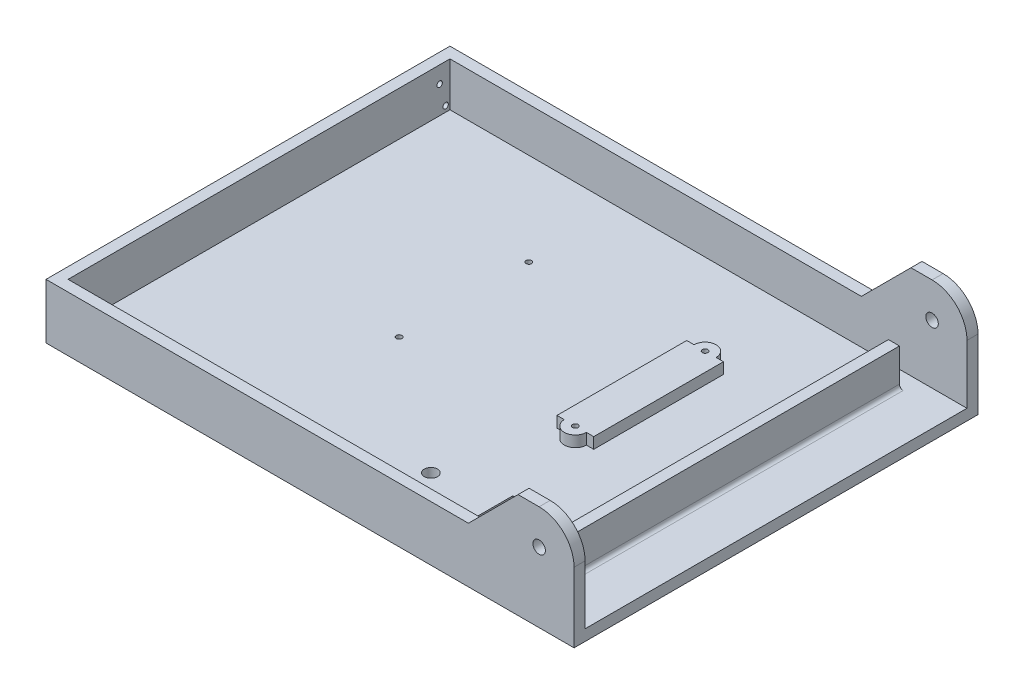
SolidWorks part; units mm, degrees
ref_plane "前视基准面" through (0, 0, 0) normal (0, 0, 1) x (1, 0, 0)
ref_plane "上视基准面" through (0, 0, 0) normal (0, 1, 0) x (1, 0, 0)
ref_plane "右视基准面" through (0, 0, 0) normal (1, 0, 0) x (0, 0, -1)
sketch "草图1" plane through (0, 0, 0) normal (0, 0, 1) x (1, 0, 0)
  line L0 (113.913, -6.4015) -> (113.913, -22.4015)
  line L1 (113.913, -22.4015) -> (104.413, -22.4015)
  line L2 (104.413, 3.0985) -> (98.6738, 3.0985)
  line L3 (104.413, -22.4015) -> (-26.7592, -22.4015)
  line L5 (-30.7592, -10.4015) -> (83.0524, -10.4015) construction
  line L6 (83.0524, -10.4015) -> (97.0524, 3.5985) construction
  line L7 (-22.7592, -21.4015) -> (-22.7592, 2.5985) construction
  line L8 (-22.7592, -21.4015) -> (-22.7592, 2.5985) construction
  line L9 (104.413, -6.4015) -> (104.413, -22.4015) construction
  line L10 (83.0524, -10.4015) -> (96.3453, 2.8914) construction
  line L11 (95.6382, 3.5985) -> (112.413, 3.5985)
  line L12 (-29.7592, 2.0985) -> (-29.7592, -9.4015)
  line L13 (-29.7592, -9.4015) -> (82.6382, -9.4015)
  line L14 (82.6382, -9.4015) -> (95.6382, 3.5985)
  line L15 (95.6382, 3.5985) -> (112.413, 3.5985) construction
  line L16 (-29.7592, 2.0985) -> (-29.7592, -9.4015) construction
  line L17 (-29.7592, -9.4015) -> (82.6382, -9.4015) construction
  line L18 (82.6382, -9.4015) -> (95.6382, 3.5985) construction
  line L20 (83.0524, -10.4015) -> (-26.7592, -10.4015)
  line L21 (-26.7592, -10.4015) -> (-26.7592, -22.4015)
  line L22 (98.6738, 3.0985) -> (85.1738, -10.4015)
  line L23 (-24.7592, -21.4015) -> (102.413, -21.4015)
  line L24 (112.413, -11.4015) -> (112.413, 3.5985)
  line L25 (112.413, 3.5985) -> (95.6382, 3.5985)
  line L26 (95.6382, 3.5985) -> (82.6382, -9.4015)
  line L27 (82.6382, -9.4015) -> (-24.7592, -9.4015)
  line L28 (-24.7592, -9.4015) -> (-24.7592, -21.4015)
  line L29 (-24.7592, -21.4015) -> (102.413, -21.4015) construction
  line L30 (112.413, -11.4015) -> (112.413, 3.5985) construction
  line L31 (112.413, 3.5985) -> (95.6382, 3.5985) construction
  line L32 (95.6382, 3.5985) -> (82.6382, -9.4015) construction
  line L33 (82.6382, -9.4015) -> (-24.7592, -9.4015) construction
  line L34 (-24.7592, -9.4015) -> (-24.7592, -21.4015) construction
  line L35 (-30.7592, 2.0985) -> (-30.7592, -10.4015) construction
  line L36 (85.1738, -10.4015) -> (83.0524, -10.4015)
  line L57 (112.413, 3.5985) -> (112.413, 5.5985)
  line L58 (112.413, 3.5985) -> (112.413, 5.5985)
  line L59 (112.413, 5.5985) -> (-32.7592, 5.5985)
  line L60 (112.413, 5.5985) -> (-32.7592, 5.5985)
  line L69 (-29.7592, -9.4015) -> (-29.7592, 2.0985) construction
  line L148 (-32.7592, 5.5985) -> (-32.7592, 2.0985)
  line L149 (-32.7592, 5.5985) -> (-32.7592, 2.0985)
  line L150 (-32.7592, 2.0985) -> (-29.7592, 2.0985)
  line L151 (-32.7592, 2.0985) -> (-29.7592, 2.0985)
  circle A0 centre (104.413, -6.4015) radius 9.5 construction
  arc A1 (113.913, -6.4015) -> (104.413, 3.0985) centre (104.413, -6.4015) ccw
  arc A2 (102.413, -21.4015) -> (112.413, -11.4015) centre (102.413, -11.4015) ccw
  arc A3 (102.413, -21.4015) -> (112.413, -11.4015) centre (102.413, -11.4015) ccw construction
  dimension "D1" = 19
  dimension "D2" = 0
  dimension "D4" = 3
  dimension "D6" = 2.5
  dimension "D7" = 1
  dimension "D3" = 0
  dimension "D5" = 1
extrude "凸台-拉伸1" add sketch "草图1" against normal offset from surface (103.9078 mm away) 1
shell "抽壳1" thickness 3
sketch "草图2" plane through (0, 0, 3) normal (0, 0, 1) x (1, 0, 0)
  line L6 (113.913, -25.4015) -> (113.913, -6.4015)
  line L7 (104.413, 3.0985) -> (98.6738, 3.0985)
  line L8 (98.6738, 3.0985) -> (85.1738, -10.4015)
  line L10 (-29.7592, -10.4015) -> (-29.7592, -25.4015)
  line L11 (-29.7592, -25.4015) -> (113.913, -25.4015)
  line L12 (113.913, -25.4015) -> (113.913, -6.4015)
  line L14 (98.6738, 3.0985) -> (85.1738, -10.4015)
  line L16 (-29.7592, -10.4015) -> (-29.7592, -25.4015)
  line L17 (-29.7592, -25.4015) -> (113.913, -25.4015)
  line L18 (104.413, 3.0985) -> (98.6738, 3.0985)
  line L21 (85.1738, -10.4015) -> (-29.7592, -10.4015)
  line L22 (85.1738, -10.4015) -> (-29.7592, -10.4015)
  circle A0 centre (104.413, -6.4015) radius 2 construction
  arc A1 (113.913, -6.4015) -> (104.413, 3.0985) centre (104.413, -6.4015) ccw
  arc A2 (113.913, -6.4015) -> (104.413, 3.0985) centre (104.413, -6.4015) ccw
  circle A3 centre (104.413, -6.4015) radius 2 construction
  dimension "D1" = 0
hole_wizard "M3 间隙孔1" positions "草图3" profile "草图4" hole size "M3" standard "GB"
sketch "草图3" plane through (0, 0, 3) normal (0, 0, 1) x (1, 0, 0)
  point P0 (104.413, -6.4015)
sketch "草图4" plane through (104.413, -6.4015, 3) normal (1, 0, 0) x (0, -1, 0)
  line L0 (0, 0) -> (0, 110.9282)
  line L1 (0, 110.9282) -> (1.7, 109.9068)
  line L2 (1.7, 109.9068) -> (1.7, 0)
  line L5 (1.7, 0) -> (0, 0)
  line L10 (0, 110.9282) -> (-1.7, 109.9068) construction
  line L11 (0, -6.35) -> (0, 107.95) construction
  dimension "孔直径" = 3.4
  dimension "孔深度" = 109.9068
  dimension "导头角度" = 118
sketch "草图6" plane through (0, -22.4015, 0) normal (0, 1, 0) x (1, 0, 0)
  line L0 (100.0439, 3.5) -> (97.0439, 3.5)
  line L1 (100.0439, 99.4078) -> (97.0439, 99.4078)
  line L2 (100.0439, 99.4078) -> (100.0439, 3.5)
  line L3 (97.0439, 3.5) -> (97.0439, 99.4078)
  line L6 (97.0439, 41.2959) -> (97.0439, 3)
  line L7 (97.0439, 85.8578) -> (97.0439, 41.2959)
  line L8 (97.0439, 99.9078) -> (97.0439, 85.8578)
  line L9 (100.0439, 99.9078) -> (97.0439, 99.9078)
  line L10 (100.0439, 3) -> (100.0439, 99.9078)
  line L11 (97.0439, 3) -> (100.0439, 3)
  line L12 (97.0439, 41.2959) -> (97.0439, 3) construction
  line L13 (97.0439, 85.8578) -> (97.0439, 41.2959) construction
  line L14 (97.0439, 99.9078) -> (97.0439, 85.8578) construction
  line L15 (100.0439, 99.9078) -> (97.0439, 99.9078) construction
  line L16 (100.0439, 3) -> (100.0439, 99.9078) construction
  line L17 (97.0439, 3) -> (100.0439, 3) construction
  dimension "D2" = 0.5
  dimension "D3" = 0.5
  dimension "D1" = 0
extrude "凸台-拉伸2" add sketch "草图6" along normal offset from surface (10 mm away) 1
sketch "草图10" plane through (0, -22.4015, 0) normal (0, 1, 0) x (1, 0, 0)
  line L0 (63.5653, 79.1078) -> (72.0573, 79.1078) construction
  line L1 (74.5549, 76.6078) -> (74.5549, 45.6078) construction
  line L2 (72.0573, 43.1078) -> (63.5653, 43.1078) construction
  line L3 (61.0676, 45.6078) -> (61.0676, 76.6078) construction
  line L4 (13.1129, 45.6078) -> (13.1129, 76.6078) construction
  line L5 (15.6106, 79.1078) -> (24.1026, 79.1078) construction
  line L6 (26.6002, 76.6078) -> (26.6002, 45.6078) construction
  line L7 (24.1026, 43.1078) -> (15.6106, 43.1078) construction
  line L8 (63.5653, 79.1078) -> (72.0573, 79.1078) construction
  line L9 (74.5549, 76.6078) -> (74.5549, 45.6078) construction
  line L10 (72.0573, 43.1078) -> (63.5653, 43.1078) construction
  line L11 (61.0676, 45.6078) -> (61.0676, 76.6078) construction
  line L12 (13.1129, 45.6078) -> (13.1129, 76.6078) construction
  line L13 (15.6106, 79.1078) -> (24.1026, 79.1078) construction
  line L14 (26.6002, 76.6078) -> (26.6002, 45.6078) construction
  line L15 (24.1026, 43.1078) -> (15.6106, 43.1078) construction
  line L16 (19.8566, 79.1078) -> (19.8566, 43.1078) construction
  line L17 (67.8113, 79.1078) -> (67.8113, 43.1078) construction
  line L18 (74.5549, 61.1078) -> (61.0676, 61.1078) construction
  line L19 (26.6002, 61.1078) -> (13.1129, 61.1078) construction
  line L21 (72.8113, 78.7578) -> (62.8113, 78.7578)
  line L22 (72.8113, 78.7578) -> (72.8113, 43.4578)
  line L23 (72.8113, 43.4578) -> (62.8113, 43.4578)
  line L24 (62.8113, 78.7578) -> (62.8113, 43.4578)
  line L25 (72.8113, 78.7578) -> (62.8113, 43.4578) construction
  line L26 (72.8113, 43.4578) -> (62.8113, 78.7578) construction
  circle A0 centre (67.8113, 43.4578) radius 3
  circle A1 centre (67.8113, 78.7578) radius 3
  ellipse E0 centre (63.5653, 76.6078) end of major axis (63.5653, 74.1078) minor radius 2.4976 (63.5653, 79.1078) -> (61.0676, 76.6078) ccw construction
  ellipse E1 centre (72.0573, 76.6078) end of major axis (72.0573, 74.1078) minor radius 2.4976 (74.5549, 76.6078) -> (72.0573, 79.1078) ccw construction
  ellipse E2 centre (72.0573, 45.6078) end of major axis (72.0573, 43.1078) minor radius 2.4976 (72.0573, 43.1078) -> (74.5549, 45.6078) ccw construction
  ellipse E3 centre (63.5653, 45.6078) end of major axis (63.5653, 43.1078) minor radius 2.4976 (61.0676, 45.6078) -> (63.5653, 43.1078) ccw construction
  ellipse E4 centre (15.6106, 45.6078) end of major axis (15.6106, 43.1078) minor radius 2.4976 (13.1129, 45.6078) -> (15.6106, 43.1078) ccw construction
  ellipse E5 centre (15.6106, 76.6078) end of major axis (15.6106, 74.1078) minor radius 2.4976 (15.6106, 79.1078) -> (13.1129, 76.6078) ccw construction
  ellipse E6 centre (24.1026, 76.6078) end of major axis (24.1026, 74.1078) minor radius 2.4976 (26.6002, 76.6078) -> (24.1026, 79.1078) ccw construction
  ellipse E7 centre (24.1026, 45.6078) end of major axis (24.1026, 43.1078) minor radius 2.4976 (24.1026, 43.1078) -> (26.6002, 45.6078) ccw construction
  ellipse E8 centre (63.5653, 76.6078) end of major axis (63.5653, 74.1078) minor radius 2.4976 (63.5653, 79.1078) -> (61.0676, 76.6078) ccw construction
  ellipse E9 centre (72.0573, 76.6078) end of major axis (72.0573, 74.1078) minor radius 2.4976 (74.5549, 76.6078) -> (72.0573, 79.1078) ccw construction
  ellipse E10 centre (72.0573, 45.6078) end of major axis (72.0573, 43.1078) minor radius 2.4976 (72.0573, 43.1078) -> (74.5549, 45.6078) ccw construction
  ellipse E11 centre (63.5653, 45.6078) end of major axis (63.5653, 43.1078) minor radius 2.4976 (61.0676, 45.6078) -> (63.5653, 43.1078) ccw construction
  ellipse E12 centre (15.6106, 45.6078) end of major axis (15.6106, 43.1078) minor radius 2.4976 (13.1129, 45.6078) -> (15.6106, 43.1078) ccw construction
  ellipse E13 centre (15.6106, 76.6078) end of major axis (15.6106, 74.1078) minor radius 2.4976 (15.6106, 79.1078) -> (13.1129, 76.6078) ccw construction
  ellipse E14 centre (24.1026, 76.6078) end of major axis (24.1026, 74.1078) minor radius 2.4976 (26.6002, 76.6078) -> (24.1026, 79.1078) ccw construction
  ellipse E15 centre (24.1026, 45.6078) end of major axis (24.1026, 43.1078) minor radius 2.4976 (24.1026, 43.1078) -> (26.6002, 45.6078) ccw construction
  point P96 (67.8113, 43.4578)
  point P97 (67.8113, 78.7578)
  point P98 (19.8566, 78.7578)
  point P99 (19.8566, 43.4578)
  point P100 (67.8113, 61.1078)
  dimension "D4" = 6
  dimension "D5" = 6
  dimension "D1" = 35.3
  dimension "D2" = 35.3
  dimension "D3" = 10
extrude "凸台-拉伸3" add sketch "草图10" along normal blind 3 contours A1 L21 L24 L23 A0 L22 | L23 A0 | L23 A0 | L21 A1 | L21 A1
sketch "草图11" plane through (0, -19.4015, 0) normal (0, 1, 0) x (1, 0, 0)
  point P0 (67.8113, 43.4578)
  point P1 (67.8113, 78.7578)
sketch "草图12" plane through (0, -22.4015, 0) normal (0, 1, 0) x (1, 0, 0)
  line L0 (63.5653, 79.1078) -> (72.0573, 79.1078) construction
  line L1 (74.5549, 76.6078) -> (74.5549, 45.6078) construction
  line L2 (72.0573, 43.1078) -> (63.5653, 43.1078) construction
  line L3 (61.0676, 45.6078) -> (61.0676, 76.6078) construction
  line L4 (113.913, 103.9078) -> (-26.7592, 103.9078)
  line L5 (-26.7592, 103.9078) -> (-26.7592, 0)
  line L6 (-26.7592, 0) -> (113.913, 0)
  line L7 (113.913, 0) -> (113.913, 103.9078)
  line L8 (113.913, 103.9078) -> (-26.7592, 103.9078)
  line L9 (-26.7592, 103.9078) -> (-26.7592, 0)
  line L10 (-26.7592, 0) -> (113.913, 0)
  line L11 (113.913, 0) -> (113.913, 103.9078)
  line L12 (63.5653, 79.1078) -> (72.0573, 79.1078)
  line L13 (74.5549, 76.6078) -> (74.5549, 45.6078)
  line L14 (72.0573, 43.1078) -> (63.5653, 43.1078)
  line L15 (61.0676, 45.6078) -> (61.0676, 76.6078)
  line L16 (15.6106, 79.1078) -> (24.1026, 79.1078) construction
  line L17 (26.6002, 76.6078) -> (26.6002, 45.6078) construction
  line L18 (24.1026, 43.1078) -> (15.6106, 43.1078) construction
  line L19 (13.1129, 45.6078) -> (13.1129, 76.6078) construction
  line L20 (15.6106, 79.1078) -> (24.1026, 79.1078) construction
  line L21 (26.6002, 76.6078) -> (26.6002, 45.6078) construction
  line L22 (24.1026, 43.1078) -> (15.6106, 43.1078) construction
  line L23 (13.1129, 45.6078) -> (13.1129, 76.6078) construction
  line L24 (19.8566, 43.1078) -> (19.8566, 79.1078) construction
  line L25 (26.6002, 61.1078) -> (13.1129, 61.1078) construction
  point P24 (19.8566, 43.4578)
  point P25 (19.8566, 78.7578)
  dimension "D2" = 35.3
  dimension "D1" = 0
hole_wizard "M2 螺纹孔的螺纹孔钻头2" positions "草图13" profile "草图14" hole size "M2" standard "GB" end condition up to next
sketch "草图13" plane through (0, -19.4015, 0) normal (0, 1, 0) x (1, 0, 0)
  point P0 (67.8113, 43.4578)
  point P3 (67.8113, 78.7578)
sketch "草图14" plane through (67.8113, -19.4015, -43.4578) normal (1, 0, 0) x (0, 0, 1)
  line L0 (0, 0) -> (0, 6)
  line L1 (0, 6) -> (0.75, 6)
  line L2 (0.75, 6) -> (0.75, 0)
  line L5 (0.75, 0) -> (0, 0)
  line L11 (0, -6.35) -> (0, 107.95) construction
  dimension "通孔孔直径" = 1.5
  dimension "通孔孔深度" = 6
hole_wizard "M2 螺纹孔的螺纹孔钻头3" positions "草图15" profile "草图16" hole size "M2" standard "GB" end condition up to next
sketch "草图15" plane through (0, -22.4015, 0) normal (0, 1, 0) x (1, 0, 0)
  point P0 (19.8566, 43.4578)
  point P3 (19.8566, 78.7578)
sketch "草图16" plane through (19.8566, -22.4015, -43.4578) normal (1, 0, 0) x (0, 0, 1)
  line L0 (0, 0) -> (0, 3)
  line L1 (0, 3) -> (0.75, 3)
  line L2 (0.75, 3) -> (0.75, 0)
  line L5 (0.75, 0) -> (0, 0)
  line L11 (0, -6.35) -> (0, 107.95) construction
  dimension "通孔孔直径" = 1.5
  dimension "通孔孔深度" = 3
sketch "草图17" plane through (0, -25.4015, 0) normal (0, -1, 0) x (1, 0, 0)
  line L0 (80.3475, -21.5157) -> (72.7475, -11.3157) construction
  line L1 (84.5475, -26.2157) -> (44.5475, -26.2157) construction
  line L2 (84.5475, -26.2157) -> (84.5475, -6.2157) construction
  line L3 (84.5475, -6.2157) -> (44.5475, -6.2157) construction
  line L4 (44.5475, -26.2157) -> (44.5475, -6.2157) construction
  line L5 (80.3475, -21.5157) -> (72.7475, -21.5157)
  line L6 (80.3475, -21.5157) -> (80.3475, -11.3157)
  line L7 (80.3475, -11.3157) -> (72.7475, -11.3157)
  line L8 (72.7475, -21.5157) -> (72.7475, -11.3157)
  line L9 (72.7475, -21.5157) -> (80.3475, -11.3157) construction
  circle A0 centre (56.1975, -15.7657) radius 1.8
  circle A1 centre (81.7175, -23.7657) radius 0.75
  point P10 (76.5475, -16.4157)
  point P11 (76.5475, -16.4157)
  point P12 (76.5475, -16.4157)
  dimension "D9" = 3.6
  dimension "D12" = 1.5
  dimension "D1" = 40
  dimension "D2" = 20
  dimension "D3" = 9.8
  dimension "D4" = 8
  dimension "D5" = 7.6
  dimension "D6" = 10.2
  dimension "D7" = 10.45
  dimension "D8" = 28.35
  dimension "D10" = 2.45
  dimension "D11" = 2.83
extrude "切除-拉伸1" cut sketch "草图17" against normal blind 3
fillet "圆角1" radius 1 1 edges at (100.0439, -22.4015, -51.4539)
sketch "Sketch1" plane through (-29.7592, 0, 0) normal (-1, 0, 0) x (0, 0, 1)
  point P0 (-101.089, -14.9563)
  point P2 (-102.7266, -20.8468)
  point P4 (-1.1812, -14.9563)
  point P6 (-2.8188, -20.8468)
hole_wizard "Tap Drill for M2 Tap1" positions "Sketch2" profile "Sketch3" hole size "M2" standard "GB"
sketch "Sketch2" plane through (-29.7592, 0, 0) normal (-1, 0, 0) x (0, 0, 1)
  point P0 (-2.8188, -20.8468)
  point P3 (-1.1812, -14.9563)
  point P6 (-102.7266, -20.8468)
  point P9 (-101.089, -14.9563)
sketch "Sketch3" plane through (-29.7592, -20.8468, -2.8188) normal (0, 1, 0) x (0, 0, 1)
  line L0 (0, 0) -> (0, 3)
  line L1 (0, 3) -> (0.75, 3)
  line L2 (0.75, 3) -> (0.75, 0)
  line L5 (0.75, 0) -> (0, 0)
  line L11 (0, -6.35) -> (0, 107.95) construction
  dimension "Thru Hole Dia." = 1.5
  dimension "Thru Hole Depth" = 3
equation "\"D2@草图10\"=\"D1@草图10\""
equation "\"D5@草图10\"=\"D4@草图10\""
